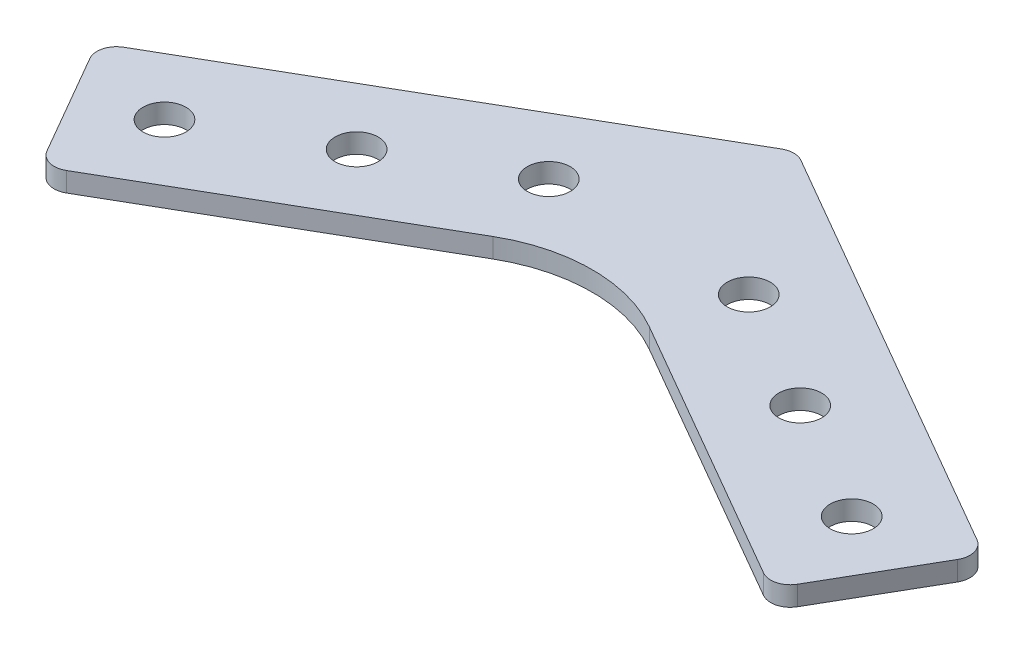
SolidWorks part; units mm, degrees
material "5052-H32"
ref_plane "Front Plane" through (0, 0, 0) normal (0, 0, 1) x (1, 0, 0)
ref_plane "Top Plane" through (0, 0, 0) normal (0, 1, 0) x (1, 0, 0)
ref_plane "Right Plane" through (0, 0, 0) normal (1, 0, 0) x (0, 0, -1)
sketch "Sketch1" plane through (0, 0, 0) normal (0, 1, 0) x (1, 0, 0)
  line L0 (-25.4, 14.6647) -> (0, 29.3294)
  line L5 (59.392, -34.29) -> (0, 0)
  line L6 (59.392, -34.29) -> (72.092, -12.293)
  line L7 (72.092, -12.293) -> (25.4, 14.6647)
  line L9 (0, 0) -> (-59.392, -34.29)
  line L11 (-25.4, 14.6647) -> (-72.092, -12.293)
  line L12 (-59.392, -34.29) -> (-72.092, -12.293)
  line L13 (0, 29.3294) -> (25.4, 14.6647)
  line L14 (-25.4, 14.6647) -> (0, 0) construction
  line L15 (25.4, 14.6647) -> (0, 0) construction
  line L16 (0, 0) -> (0, 29.3294) construction
  dimension "D1" = 25.4
  dimension "D2" = 25.4
  dimension "D5" = 120
  dimension "D3" = 68.58
  dimension "D4" = 68.58
extrude "Boss-Extrude1" add sketch "Sketch1" along normal blind 3.175 contours L0 L13 L7 L6 L5 L9 L12 L11
sketch "Sketch2" plane through (0, 3.175, 0) normal (0, 1, 0) x (1, 0, 0)
  line L0 (-72.092, -12.293) -> (-59.392, -34.29) construction
  line L1 (-55.8434, -17.5765) -> (-65.742, -23.2915) construction
  line L2 (72.092, -12.293) -> (59.392, -34.29) construction
  line L3 (55.8434, -17.5765) -> (65.742, -23.2915) construction
  circle A0 centre (-55.8434, -17.5765) radius 3.4925
  circle A1 centre (55.8434, -17.5765) radius 3.4925
  dimension "D1" = 6.985
  dimension "D2" = 11.43
sketch "Sketch7" plane through (0, 3.175, 0) normal (0, 1, 0) x (1, 0, 0)
  line L0 (-72.092, -12.293) -> (-59.392, -34.29) construction
  line L1 (-55.8434, -17.5765) -> (-65.742, -23.2915) construction
  line L2 (72.092, -12.293) -> (59.392, -34.29) construction
  line L3 (55.8434, -17.5765) -> (65.742, -23.2915) construction
  circle A0 centre (-55.8434, -17.5765) radius 3.4925
  circle A1 centre (55.8434, -17.5765) radius 3.4925
  dimension "D1" = 6.985
  dimension "D2" = 11.43
extrude "Cut-Extrude2" cut sketch "Sketch2" against normal blind 3.175 contours A0
pattern_linear "LPattern5" count 3 spacing 22.86 along (0.866, 0, -0.5) of "Cut-Extrude2"
extrude "Cut-Extrude3" cut sketch "Sketch7" against normal blind 3.175 contours A1
pattern_linear "LPattern6" count 3 spacing 22.86 along (-0.866, 0, -0.5) of "Cut-Extrude3"
fillet "Fillet1" radius 3.175 4 edges at (-59.392, 1.5875, 34.29) (-72.092, 1.5875, 12.293) (72.092, 1.5875, 12.293) (59.392, 1.5875, 34.29)
fillet "Fillet3" radius 3.175 1 edges at (0, 1.5875, -29.3294)
fillet "Fillet4" radius 25.4 1 edges at (0, 1.5875, 0)
equation "\"InnerAngle\"= \"AngleBC@Assem2.SLDASM\""
equation "\"StockThickness\"= .125in"
equation "\"HoleDiameter\"= .275in"
equation "\"BarWidth\"= 1in"
equation "\"HoleSpacing\"=0.9"
equation "\"AdditionalHoleCount\"= 3"
equation "\"D1@Sketch1\"=\"BarWidth\""
equation "\"D2@Sketch1\"= \"BarWidth\""
equation "\"WingLength\"= ( \"AdditionalHoleCount\" ) * \"HoleSpacing\""
equation "\"D5@Sketch1\"=\"InnerAngle\""
equation "\"D1@Boss-Extrude1\"=\"StockThickness\""
equation "\"D1@Sketch2\"=\"HoleDiameter\""
equation "\"D2@Sketch2\"=\"HoleSpacing\"/2"
equation "\"D3@LPattern5\"=\"HoleSpacing\""
equation "\"D1@LPattern5\"=\"AdditionalHoleCount\""
equation "\"D2@Sketch7\"=\"HoleSpacing\"/2"
equation "\"D1@Sketch7\"=\"HoleDiameter\""
equation "\"D3@LPattern6\"=\"HoleSpacing\""
equation "\"D1@LPattern6\"=\"AdditionalHoleCount\""
equation "\"D3@Sketch1\"=\"WingLength\""
equation "\"D4@Sketch1\"=\"WingLength\""
